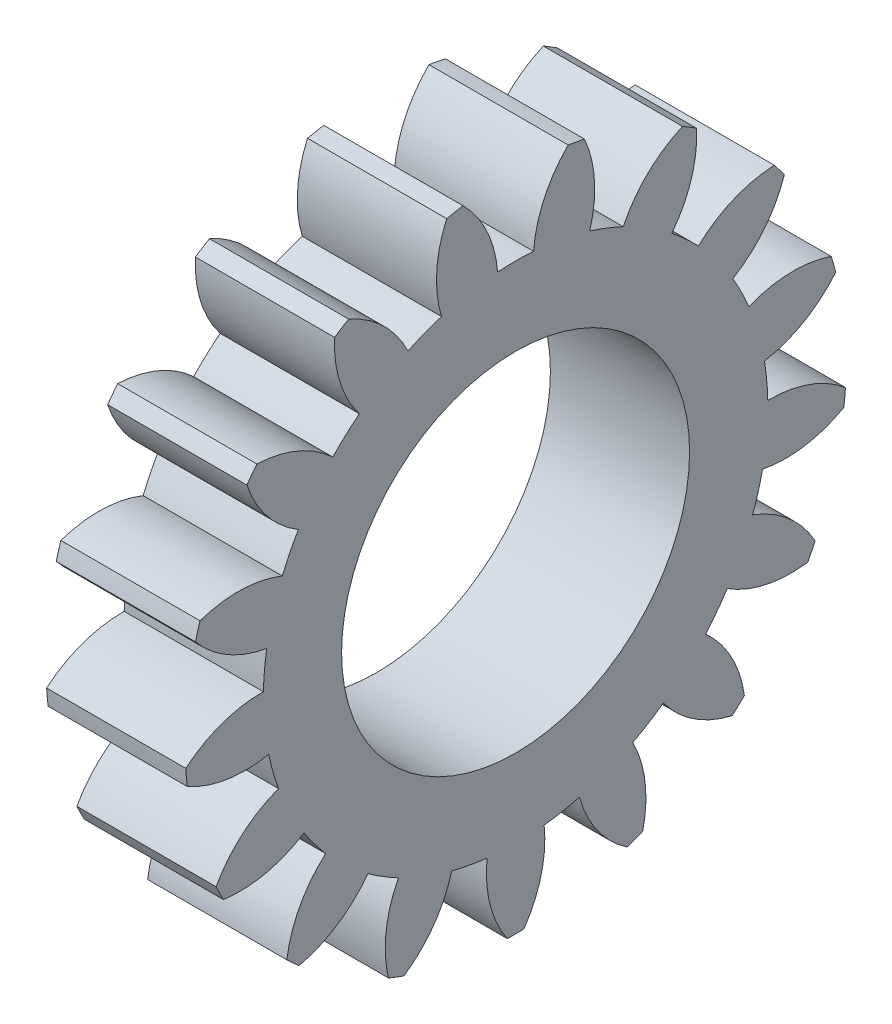
SolidWorks part; units mm, degrees
ref_plane "Plane1" through (0, 0, 0) normal (0, 0, 1) x (1, 0, 0)
ref_plane "Plane2" through (0, 0, 0) normal (0, 1, 0) x (1, 0, 0)
ref_plane "Plane3" through (0, 0, 0) normal (1, 0, 0) x (0, 0, -1)
sketch "HoldingSke" plane through (0, 0, 0) normal (0, 1, 0) x (1, 0, 0)
  line L0 (0, 0) -> (0.9563, -0.2924)
  line L1 (-15, 0) -> (100, 0) construction
  line L2 (0, 0) -> (-2.1039, 2.3779)
  line L3 (0, 0) -> (-11.863, 4.5341)
  line L4 (0, 0) -> (8.2586, 2.5249)
  line L5 (0, 0) -> (-46.8476, -17.4728)
  line L6 (0, 0) -> (-3.3159, -2.2372)
  line L7 (-2.1039, 2.3779) -> (8.6586, 51.2059)
  line L8 (-76.2, 54.61) -> (-74.4, 54.61)
  line L9 (-71.009, 38.7566) -> (-53.1078, 45.2721)
  line L10 (-76.2, 71.12) -> (104.1128, 71.12)
  line L11 (0, 0) -> (-4, 0)
  line L12 (-76.2, 101.6) -> (-76.162, 101.6)
  line L13 (24.9733, 27.94) -> (52.9518, 28.4284)
  line L14 (24.9733, 27.94) -> (24.9743, 27.94)
  line L15 (24.9733, 27.94) -> (100.4006, 29.5858)
  line L16 (-63.627, -1) -> (-12.827, -1)
  circle A0 centre (0, 0) radius 5
  circle A1 centre (0, 0) radius 7.249
  circle A2 centre (0, 0) radius 37.5
  circle A3 centre (0, 0) radius 5
  dimension "MHD" = 14.498
  dimension "Hub_dia" = 75
  dimension "Bore" = 10
  dimension "MBD" = 10
  dimension "Num_teeth" = 17
  dimension "Pitch" = 1
  dimension "Overall_len" = 50
  dimension "Show_teeth" = 17
  dimension "Thickness" = 4
  dimension "OAL" = 50.0001
  dimension "T_dim" = 1.8
  dimension "Ap" = 20
  dimension "H" = 19.05
  dimension "Pitch_radius" = 180.3128
  dimension "Width" = 4
  dimension "Backlash" = 0.038
  dimension "Addendum_fac" = 1
  dimension "Dedendum_fac" = 1.25
  dimension "Clearance_fac" = 0.25
  dimension "Dedendum_add" = 0.001
  dimension "Module" = 1
sketch "BasProSke" plane through (0, 0, 0) normal (0, 1, 0) x (1, 0, 0)
  line L0 (-10, 0) -> (60, 0) construction
  line L1 (0, 0) -> (0, 9.5)
  line L2 (0, 0) -> (4, 0)
  line L3 (4, 0) -> (4, 9.5)
  line L4 (4, 9.5) -> (0, 9.5)
  dimension "Thickness" = 4
  dimension "Diameter" = 19
revolve "Base-Revolve" add sketch "BasProSke" angle 360 about L0
sketch "TooCutSke" plane through (0, 0, 0) normal (1, 0, 0) x (0, 0, -1)
  line L1 (0, 0) -> (0, 107) construction
  line L2 (0, 0) -> (-0.8507, 8.4573) construction
  line L3 (0, 0) -> (-3.1126, 16.6509) construction
  line L4 (-0.8507, 8.4573) -> (-1.5563, 8.3254) construction
  arc A0 (0.5169, 7.2306) -> (-0.5169, 7.2306) centre (0, 0) ccw
  arc A1 (1.5331, 9.4012) -> (-1.5331, 9.4012) centre (0, 0) ccw
  circle A2 centre (0, 0) radius 8.5 construction
  circle A3 centre (0, 0) radius 7.9874 construction
  arc A4 (-0.5169, 7.2306) -> (-1.5331, 9.4012) centre (-3.9066, 6.9668) ccw
  arc A5 (1.5331, 9.4012) -> (0.5169, 7.2306) centre (3.9066, 6.9668) ccw
  dimension "Root_dia" = 14.498
  dimension "Overcut_dia" = 19.0508
  dimension "Pitch_dia" = 17
  dimension "Base_dia" = 15.9748
  dimension "Flank_rad" = 3.4
  dimension "Half_ang" = 10.588
  dimension "Half_CT" = 0.7178
extrude "ToothCut" cut sketch "TooCutSke" along normal through all
fillet "Breaks" [suppressed] radius 0.02
fillet "RootFillets" [suppressed] radius 0.251
pattern_circular "TeethCuts" count 17 every 21.176 about axis through (-10, 0, 0) along (1, 0, 0) of "ToothCut", "RootFillets", "Breaks"
sketch "HubNeaOneSke" plane through (0, 0, 0) normal (-1, 0, 0) x (0, 0, 1)
  circle A0 centre (0, 0) radius 7.249
  dimension "Diameter" = 14.498
extrude "HubNearOne" [suppressed] add sketch "HubNeaOneSke" along normal blind 46.0001
sketch "HubNeaBotSke" plane through (0, 0, 0) normal (-1, 0, 0) x (0, 0, 1)
  circle A0 centre (0, 0) radius 7.249
  dimension "Diameter" = 14.498
extrude "HubNearBoth" [suppressed] add sketch "HubNeaBotSke" along normal blind 23
ref_plane "FarPln" through (4, 0, 0) normal (1, 0, 0) x (0, 0, -1)
sketch "HubFarSke" plane through (4, 0, 0) normal (1, 0, 0) x (0, 0, -1)
  circle A0 centre (0, 0) radius 7.249
  dimension "Diameter" = 14.498
extrude "HubFar" [suppressed] add sketch "HubFarSke" along normal blind 23
sketch "BorSke" plane through (0, 0, 0) normal (1, 0, 0) x (0, 0, -1)
  circle A0 centre (0, 0) radius 5
  dimension "Diameter" = 10
extrude "Bore" cut sketch "BorSke" along normal mid plane 100.0001
sketch "KeySke" plane through (0, 0, 0) normal (1, 0, 0) x (0, 0, -1)
  line L0 (-2, 0) -> (-2, 6.8)
  line L1 (-2, 6.8) -> (2, 6.8)
  line L2 (2, 6.8) -> (2, 0)
  line L3 (0, 0) -> (0, 34) construction
  line L4 (-2, 0) -> (2, 0)
  dimension "Width" = 4
  dimension "Offset" = 6.8
extrude "Keyway" [suppressed] cut sketch "KeySke" along normal mid plane 100.0001
pattern_circular "Keyway2" [suppressed] count 2 every 90 about axis through (-10, 0, 0) along (1, 0, 0)
sketch "Sketch1" plane through (4, 0, 0) normal (1, 0, 0) x (0, 0, -1)
  circle A0 centre (0, 0) radius 9.5
equation "' \"Module@HoldingSke\" = 6.35"
equation "' \"Num_teeth@HoldingSke\" = 12"
equation "' \"Ap@HoldingSke\" =  20"
equation "' \"Ap@HoldingSke\" = 20"
equation "' \"Width@HoldingSke\" = 0.5 * 25.4"
equation "' \"Hub_dia@HoldingSke\"= 1 * 25.4"
equation "' \"Hub_dia@HoldingSke\" = 1 * 25.4"
equation "' \"Overall_len@HoldingSke\" = 1.0 * 25.4"
equation "' \"Bore@HoldingSke\" = 0.75 * 25.4"
equation "' \"T_dim@HoldingSke\" = 0.1 * 25.4"
equation "' \"Width@KeySke\" = 0.25 * 25.4"
equation "' \"Show_teeth@HoldingSke\" = 13"
equation "' \"Backlash@HoldingSke\" = 0.009 * 25.4"
equation "' \"Addendum_fac@HoldingSke\" = 1.0"
equation "' \"Dedendum_fac@HoldingSke\" = 1.25"
equation "' \"Dedendum_add@HoldingSke\" = 0.00005 * 25.4"
equation "' \"Clearance_fac@HoldingSke\" = 0.25"
equation "\"Pitch@HoldingSke\" = 1 / \"Module@HoldingSke\""
equation "\"Overcut_dia@TooCutSke\" = (\"Num_teeth@HoldingSke\" + 2 * \"Addendum_fac@HoldingSke\") / \"Pitch@HoldingSke\" + 0.002 * 25.4"
equation "\"Pitch_dia@TooCutSke\" = \"Num_teeth@HoldingSke\" / \"Pitch@HoldingSke\""
equation "\"Base_dia@TooCutSke\" = \"Num_teeth@HoldingSke\" / \"Pitch@HoldingSke\" * cos((\"Ap@HoldingSke\"  * 3.14159265 / 180))"
equation "\"Root_dia@TooCutSke\" = (\"Num_teeth@HoldingSke\" + 2) / \"Pitch@HoldingSke\" - 2 * (\"Addendum_fac@HoldingSke\" + \"Dedendum_fac@HoldingSke\") / \"Pitch@HoldingSke\" - \"Dedendum_add@HoldingSke\" * 2"
equation "\"Half_ang@TooCutSke\" = 180 / \"Num_teeth@HoldingSke\""
equation "\"Half_CT@TooCutSke\" = \"Num_teeth@HoldingSke\" / \"Pitch@HoldingSke\" * sin((3.14159265 / 2 / \"Num_teeth@HoldingSke\")) / 2 - 7 * \"Backlash@HoldingSke\" / 4"
equation "\"Flank_rad@TooCutSke\" = \"Num_teeth@HoldingSke\" / \"Pitch@HoldingSke\" / 5"
equation "\"Radius@RootFillets\" = \"Clearance_fac@HoldingSke\" / \"Pitch@HoldingSke\" + \"Dedendum_add@HoldingSke\""
equation "\"Break_rad@Breaks\" = 0.02 / \"Pitch@HoldingSke\""
equation "\"Thickness@HoldingSke\" = \"Width@HoldingSke\""
equation "\"OAL@HoldingSke\" = \"Thickness@HoldingSke\""
equation "\"MHD@HoldingSke\" = (\"Num_teeth@HoldingSke\" + 2) / \"Pitch@HoldingSke\" - 2 * (\"Addendum_fac@HoldingSke\" + \"Dedendum_fac@HoldingSke\")  / \"Pitch@HoldingSke\" - \"Dedendum_add@HoldingSke\" * 2"
equation "\"MBD@HoldingSke\" = (\"Num_teeth@HoldingSke\" + 2) / \"Pitch@HoldingSke\" - 2 * (\"Addendum_fac@HoldingSke\" + \"Dedendum_fac@HoldingSke\")  / \"Pitch@HoldingSke\" - \"Dedendum_add@HoldingSke\" * 2 - 0.002 * 25.4"
equation "\"MHD@HoldingSke\" = ((sgn( \"MHD@HoldingSke\" - \"Hub_dia@HoldingSke\" )-1)*( \"MHD@HoldingSke\" - \"Hub_dia@HoldingSke\" ))/-2+ \"Hub_dia@HoldingSke\""
equation "\"MBD@HoldingSke\" = ((sgn( \"MBD@HoldingSke\" - \"Bore@HoldingSke\" )-1)*( \"MBD@HoldingSke\" - \"Bore@HoldingSke\" ))/-2+ \"Bore@HoldingSke\""
equation "\"OAL@HoldingSke\" = ((sgn( \"OAL@HoldingSke\" - \"Overall_len@HoldingSke\" )+1)*( \"OAL@HoldingSke\" - \"Overall_len@HoldingSke\" ))/2 + \"Overall_len@HoldingSke\" + 0.000002 * 25.4"
equation "\"Num_teeth@TeethCuts\" = int( \"Show_teeth@HoldingSke\" ) + 1"
equation "\"Num_teeth@TeethCuts\" = ((sgn( \"Num_teeth@TeethCuts\" - \"Num_teeth@HoldingSke\" )-1)*( \"Num_teeth@TeethCuts\" - \"Num_teeth@HoldingSke\" ))/-2+ \"Num_teeth@HoldingSke\""
equation "\"Num_teeth@TeethCuts\" = ((sgn( \"Num_teeth@TeethCuts\" - 2.0)+1)*( \"Num_teeth@TeethCuts\" - 2.0))/2 +2.0"
equation "\"Angle@TeethCuts\" = 360.0 / \"Num_teeth@HoldingSke\""
equation "\"Diameter@BasProSke\" = (\"Num_teeth@HoldingSke\" + 2 * \"Addendum_fac@HoldingSke\") / \"Pitch@HoldingSke\""
equation "\"Thickness@BasProSke\"  = \"Thickness@HoldingSke\""
equation "' \"Fillet_rad@BasProSke\" =  \"Thickness@HoldingSke\" * 0.05"
equation "' \"Fillet_rad@BasProSke\" = \"Thickness@HoldingSke\" * 0.05"
equation "\"MHD@HoldingSke\" = ((sgn( \"MHD@HoldingSke\" - \"Root_dia@TooCutSke\" )-1)*( \"MHD@HoldingSke\" - \"Root_dia@TooCutSke\" ))/-2+ \"Root_dia@TooCutSke\""
equation "\"Diameter@HubNeaOneSke\" = \"MHD@HoldingSke\""
equation "\"Length@HubNearOne\" = \"OAL@HoldingSke\" - \"Thickness@BasProSke\""
equation "\"Diameter@HubNeaBotSke\" = \"MHD@HoldingSke\""
equation "\"Length@HubNearBoth\" = ( \"OAL@HoldingSke\" - \"Thickness@BasProSke\" ) / 2.0"
equation "\"Thickness@FarPln\" = \"Thickness@BasProSke\""
equation "\"Diameter@HubFarSke\" = \"MHD@HoldingSke\""
equation "\"Length@HubFar\" = ( \"OAL@HoldingSke\" - \"Thickness@BasProSke\" ) / 2.0"
equation "\"Diameter@BorSke\" = \"MBD@HoldingSke\""
equation "\"D1@Bore\" = \"OAL@HoldingSke\" * 2.0"
equation "\"D1@Keyway\" = \"OAL@HoldingSke\" * 2.0"
equation "\"Offset@KeySke\" = \"T_dim@HoldingSke\" + \"MBD@HoldingSke\" / 2.0"
